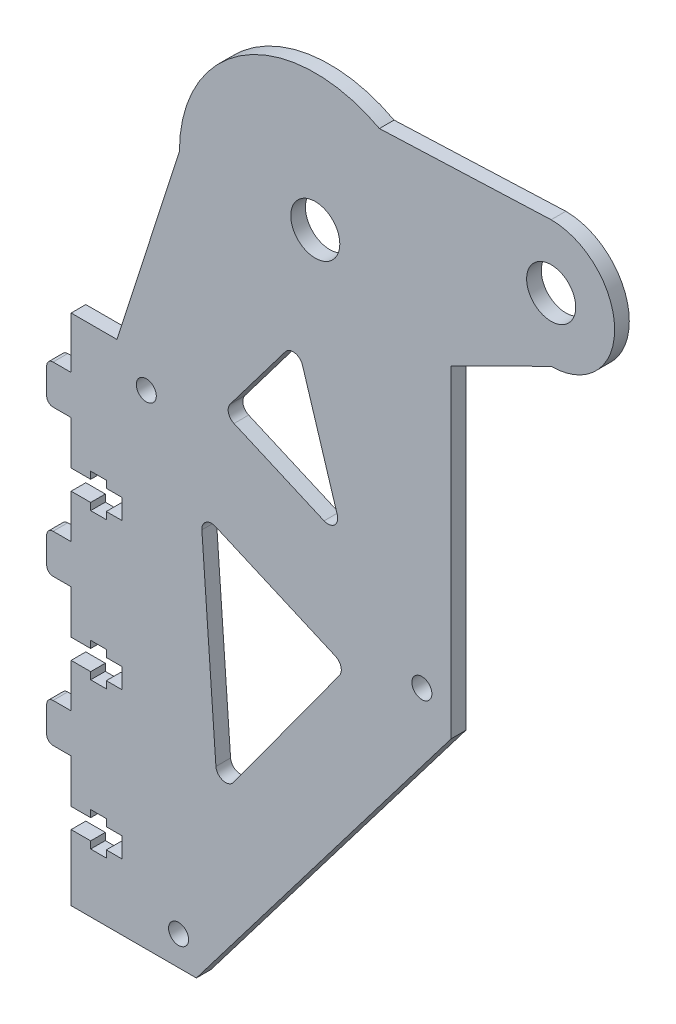
SolidWorks part; units mm, degrees
ref_plane "前视基准面" through (0, 0, 0) normal (0, 0, 1) x (1, 0, 0)
ref_plane "上视基准面" through (0, 0, 0) normal (0, 1, 0) x (1, 0, 0)
ref_plane "右视基准面" through (0, 0, 0) normal (1, 0, 0) x (0, 0, -1)
sketch "草图1" plane through (0, 0, 0) normal (0, 0, 1) x (1, 0, 0)
  line L4 (298.5456, -83.8944) -> (298.5456, -92.8418)
  line L11 (348.537, 4.3962) -> (298.542, 5.1056) construction
  line L15 (298.5456, -96.9418) -> (302.5456, -96.9418)
  line L16 (302.5456, -96.9418) -> (302.5456, -98.3918)
  line L17 (302.5456, -98.3918) -> (305.7456, -98.3918)
  line L18 (305.7456, -98.3918) -> (305.7456, -96.9418)
  line L19 (305.7456, -96.9418) -> (308.9456, -96.9418)
  line L20 (308.9456, -96.9418) -> (308.9456, -92.8418)
  line L21 (308.9456, -92.8418) -> (305.7456, -92.8418)
  line L22 (305.7456, -92.8418) -> (305.7456, -91.3918)
  line L23 (305.7456, -91.3918) -> (302.5456, -91.3918)
  line L24 (302.5456, -91.3918) -> (302.5456, -92.8418)
  line L25 (302.5456, -92.8418) -> (298.5456, -92.8418)
  line L27 (298.5456, -94.8944) -> (302.5431, -94.8944) construction
  line L28 (298.5456, -109.8944) -> (303.5456, -109.8944) construction
  line L29 (303.5456, -113.8944) -> (293.5456, -113.8944) construction
  line L30 (303.5456, -113.8944) -> (303.5456, -105.8944) construction
  line L31 (303.5456, -105.8944) -> (293.5456, -105.8944) construction
  line L32 (293.5456, -113.8944) -> (293.5456, -105.8944)
  line L33 (303.5456, -113.8944) -> (293.5456, -105.8944) construction
  line L34 (303.5456, -105.8944) -> (293.5456, -113.8944) construction
  line L35 (302.5456, -126.947) -> (298.5456, -126.947)
  line L36 (298.5456, -122.847) -> (302.5456, -122.847)
  line L37 (302.5456, -128.397) -> (302.5456, -126.947)
  line L38 (305.7456, -128.397) -> (302.5456, -128.397)
  line L39 (305.7456, -126.947) -> (305.7456, -128.397)
  line L40 (308.9456, -126.947) -> (305.7456, -126.947)
  line L41 (308.9456, -122.847) -> (308.9456, -126.947)
  line L42 (305.7456, -122.847) -> (308.9456, -122.847)
  line L43 (305.7456, -121.397) -> (305.7456, -122.847)
  line L44 (302.5456, -121.397) -> (305.7456, -121.397)
  line L45 (302.5456, -122.847) -> (302.5456, -121.397)
  line L46 (293.5456, -75.8944) -> (293.5456, -83.8944)
  line L47 (302.5456, -62.8418) -> (298.5456, -62.8418)
  line L48 (298.5456, -66.9418) -> (302.5456, -66.9418)
  line L49 (302.5456, -66.9418) -> (302.5456, -68.3918)
  line L50 (302.5456, -68.3918) -> (305.7456, -68.3918)
  line L51 (305.7456, -68.3918) -> (305.7456, -66.9418)
  line L52 (305.7456, -66.9418) -> (308.9456, -66.9418)
  line L53 (308.9456, -66.9418) -> (308.9456, -62.8418)
  line L54 (308.9456, -62.8418) -> (305.7456, -62.8418)
  line L55 (305.7456, -62.8418) -> (305.7456, -61.3918)
  line L56 (305.7456, -61.3918) -> (302.5456, -61.3918)
  line L57 (302.5456, -61.3918) -> (302.5456, -62.8418)
  line L58 (293.5456, -83.8944) -> (298.5456, -83.8944)
  line L59 (293.5456, -75.8944) -> (298.5456, -75.8944)
  line L60 (298.5456, -75.8944) -> (298.5456, -66.9418)
  line L63 (298.5456, -105.8944) -> (293.5456, -105.8944)
  line L64 (293.5456, -113.8944) -> (298.5456, -113.8944)
  line L65 (298.5456, -113.8944) -> (298.5456, -122.847)
  line L66 (308.9456, -64.8918) -> (305.2429, -64.8918) construction
  line L67 (293.5456, -45.8892) -> (298.5456, -45.8892)
  line L68 (293.5456, -53.8892) -> (293.5456, -45.8892)
  line L69 (293.5456, -53.8892) -> (298.5456, -53.8892)
  line L70 (298.5456, -53.8892) -> (298.5456, -62.8418)
  line L78 (298.5456, -126.947) -> (298.5456, -140.447)
  line L79 (298.5456, -140.447) -> (324.1889, -140.447)
  line L81 (376.3586, 4.3962) -> (376.3586, -71.947)
  line L84 (376.3586, -71.947) -> (324.1889, -140.447)
  line L85 (298.5456, -45.8892) -> (298.5456, -35.347)
  line L87 (298.5456, -35.347) -> (307.937, -35.347)
  line L88 (307.937, -35.347) -> (320.7154, 4.3962)
  line L89 (320.5456, -134.447) -> (313.937, -41.347) construction
  line L90 (313.937, -41.347) -> (370.3586, -65.947) construction
  line L91 (370.3586, -65.947) -> (320.5456, -134.447) construction
  line L92 (354.9473, -70.1368) -> (328.5796, -106.3961)
  line L93 (328.5796, -106.3961) -> (325.0814, -57.1152)
  line L94 (325.0814, -57.1152) -> (354.9473, -70.1368)
  line L95 (370.3586, -65.947) -> (348.537, 4.3962) construction
  line L96 (348.537, 4.3962) -> (313.937, -41.347) construction
  line L97 (329.5711, -37.2544) -> (354.3373, -48.0525)
  line L98 (354.3373, -48.0525) -> (344.7587, -17.1754)
  line L99 (344.7587, -17.1754) -> (329.5711, -37.2544)
  line L100 (348.537, 4.3962) -> (337.1349, 16.1265) construction
  line L101 (298.5456, -96.9418) -> (298.5456, -105.8944)
  line L104 (376.3586, -71.947) -> (376.3586, -11.3546) construction
  circle A11 centre (348.537, 4.3962) radius 5.0225
  circle A14 centre (348.537, 4.3962) radius 27.8216 construction
  circle A23 centre (348.5373, 24.4573) radius 2.05 construction
  circle A24 centre (320.5456, -134.447) radius 2.05
  circle A25 centre (370.3586, -65.947) radius 2.05
  circle A26 centre (313.937, -41.347) radius 2.05
  circle A27 centre (348.537, 4.3962) radius 12 construction
  circle A28 centre (340.173, 13.001) radius 1.65 construction
  arc A39 (320.7154, 4.3962) -> (376.3586, 4.3962) centre (348.537, 4.3962) cw
  circle A43 centre (357.1418, 12.7602) radius 1.65 construction
  circle A44 centre (356.901, -4.2086) radius 1.65 construction
  circle A45 centre (339.9322, -3.9678) radius 1.65 construction
  point P20 (300.5444, -94.8944)
  point P30 (298.5456, -109.8944)
  dimension "D3" = 4.1
  dimension "D4" = 10.045
  dimension "D5" = 3.2
  dimension "D6" = 50
  dimension "D15" = 22
  dimension "D17" = 6
  dimension "D19" = 6
  dimension "D23" = 24
  dimension "D25" = 3.3
  dimension "D7" = 4
  dimension "D8" = 4
  dimension "D9" = 2.0526
  dimension "D10" = 15
  dimension "D11" = 8
  dimension "D12" = 10
  dimension "D13" = 100
  dimension "D14" = 13.5
  dimension "D16" = 6
  dimension "D18" = 6
  dimension "D20" = 6
  dimension "D24" = 45
  dimension "D30" = 7
  dimension "D21" = 10
  dimension "D22" = 10
extrude "凸台-拉伸1" add sketch "草图1" along normal blind 3
sketch "草图2" plane through (298.5456, 0, 0) normal (-1, 0, 0) x (0, 0, 1)
  line L0 (1.5, -66.9418) -> (1.5, -62.8418)
  line L1 (3, -66.9418) -> (0, -66.9418) construction
  line L2 (3, -62.8418) -> (0, -62.8418) construction
  circle A0 centre (1.5, -64.8918) radius 2.05
fillet "圆角1" radius 2 6 edges at (344.7587, -17.1754, 1.5) (329.5711, -37.2544, 1.5) (354.3373, -48.0525, 1.5) (325.0814, -57.1152, 1.5) (328.5796, -106.3961, 1.5) (354.9473, -70.1368, 1.5)
fillet "圆角2" radius 1.3 6 edges at (293.5456, -45.8892, 1.5) (293.5456, -53.8892, 1.5) (293.5456, -83.8944, 1.5) (293.5456, -75.8944, 1.5) (293.5456, -113.8944, 1.5) (293.5456, -105.8944, 1.5)
sketch "草图3" plane through (0, 0, 0) normal (0, 0, -1) x (-1, 0, 0)
  line L0 (-348.537, 4.3962) -> (-396.8333, 17.3372) construction
  line L1 (-396.8333, 30.3372) -> (-348.537, 28.3962)
  line L2 (-396.8333, 4.3372) -> (-348.537, -19.6038)
  line L3 (-348.537, 28.3962) -> (-372.537, 4.3962)
  line L4 (-372.537, 4.3962) -> (-347.9688, -20.172)
  line L5 (-348.537, 4.3962) -> (-348.537, -38.7587) construction
  circle A0 centre (-396.8333, 17.3372) radius 5.025
  circle A1 centre (-396.8333, 17.3372) radius 13 construction
  circle A3 centre (-348.537, 4.3962) radius 24 construction
  arc A4 (-396.8333, 30.3372) -> (-396.8333, 4.3372) centre (-396.8333, 17.3372) ccw
  dimension "D1" = 10.05
  dimension "D2" = 105
  dimension "D3" = 50
extrude "凸台-拉伸2" add sketch "草图3" against normal blind 3 contours L1 A4 L2 L4 L3 A0
